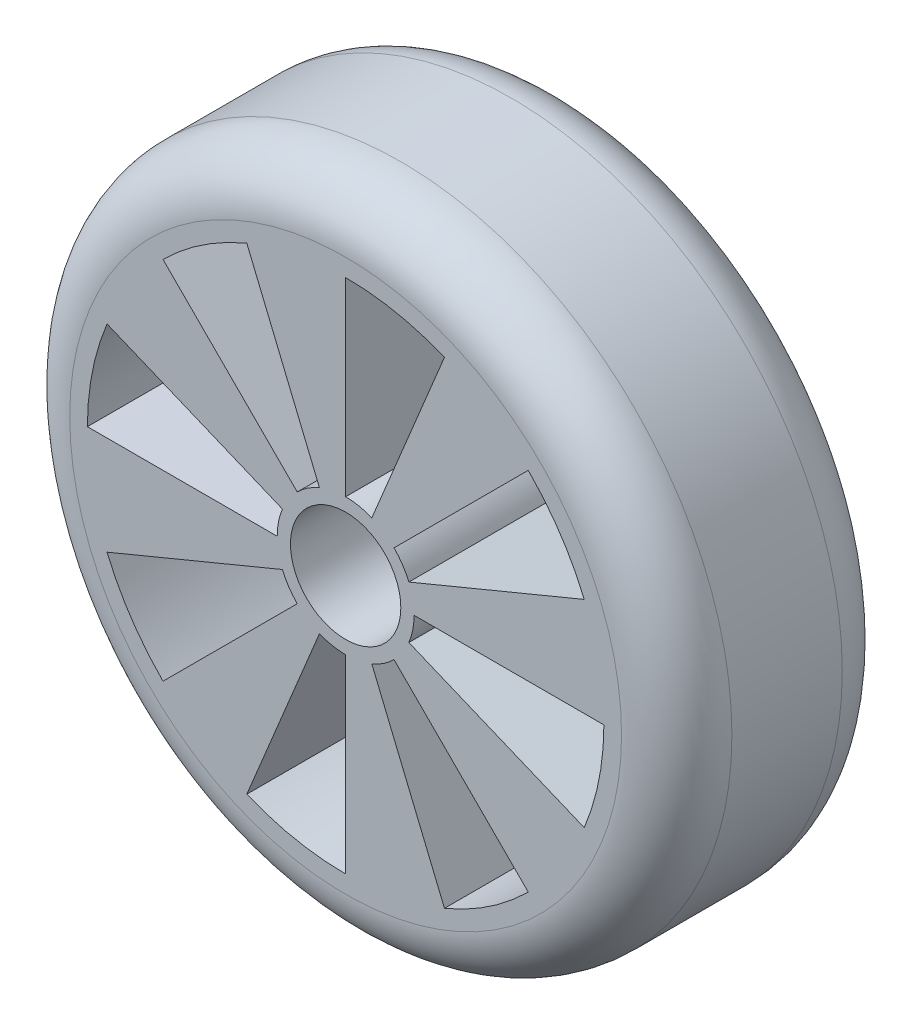
SolidWorks part; units mm, degrees
ref_plane "Front Plane" through (0, 0, 0) normal (0, 0, 1) x (1, 0, 0)
ref_plane "Top Plane" through (0, 0, 0) normal (0, 1, 0) x (1, 0, 0)
ref_plane "Right Plane" through (0, 0, 0) normal (1, 0, 0) x (0, 0, -1)
sketch "Sketch1" plane through (0, 0, 0) normal (0, 0, 1) x (1, 0, 0)
  circle A0 centre (0, 0) radius 150
  dimension "D1" = 300
extrude "Boss-Extrude1" add sketch "Sketch1" along normal blind 100
fillet "Fillet1" radius 25 2 edges at (150, 0, 0) (150, 0, 100)
sketch "Sketch3" plane through (0, 0, 0) normal (0, 0, 1) x (1, 0, 0)
  circle A0 centre (0, 0) radius 25
  circle A1 centre (0, 0) radius 31
  circle A2 centre (0, 0) radius 117
  dimension "D1" = 50
  dimension "D2" = 62
  dimension "D3" = 234
sketch "Sketch4" plane through (0, 0, 0) normal (0, 0, 1) x (1, 0, 0)
  line L0 (0, 0) -> (0, 117)
  line L1 (0, 0) -> (44.774, 108.0939)
  line L2 (0, 0) -> (82.7315, 82.7315)
  line L3 (0, 0) -> (108.0939, 44.774)
  line L4 (0, 0) -> (117, 0)
  line L5 (0, 0) -> (108.0939, -44.774)
  line L6 (0, 0) -> (82.7315, -82.7315)
  line L7 (0, 0) -> (44.774, -108.0939)
  line L8 (0, 0) -> (0, -117)
  line L9 (0, 0) -> (-44.774, -108.0939)
  line L10 (0, 0) -> (-82.7315, -82.7315)
  line L11 (0, 0) -> (-108.0939, -44.774)
  line L12 (0, 0) -> (-117, 0)
  line L13 (0, 0) -> (-108.0939, 44.774)
  line L14 (0, 0) -> (-82.7315, 82.7315)
  line L15 (0, 0) -> (-44.774, 108.0939)
  circle A0 centre (0, 0) radius 31
  circle A1 centre (0, 0) radius 117
  point P23 (0, 0)
  dimension "D1" = 62
  dimension "D2" = 234
  dimension "D3" = 16
extrude "Cut-Extrude1" cut sketch "Sketch4" against normal blind 300 and the other way blind 300 contours L3 A1 L2 A0 | L1 A1 L0 A0 | L15 A1 L14 A0 | L13 A1 L12 A0 | L11 A1 L10 A0 | L9 A1 L8 A0 | L7 A1 L6 A0 | L5 A1 L4 A0
sketch "Sketch5" plane through (0, 0, 0) normal (0, 0, 1) x (1, 0, 0)
  circle A0 centre (0, 0) radius 25
  dimension "D1" = 50
extrude "Cut-Extrude2" cut sketch "Sketch5" against normal blind 300 and the other way blind 300
